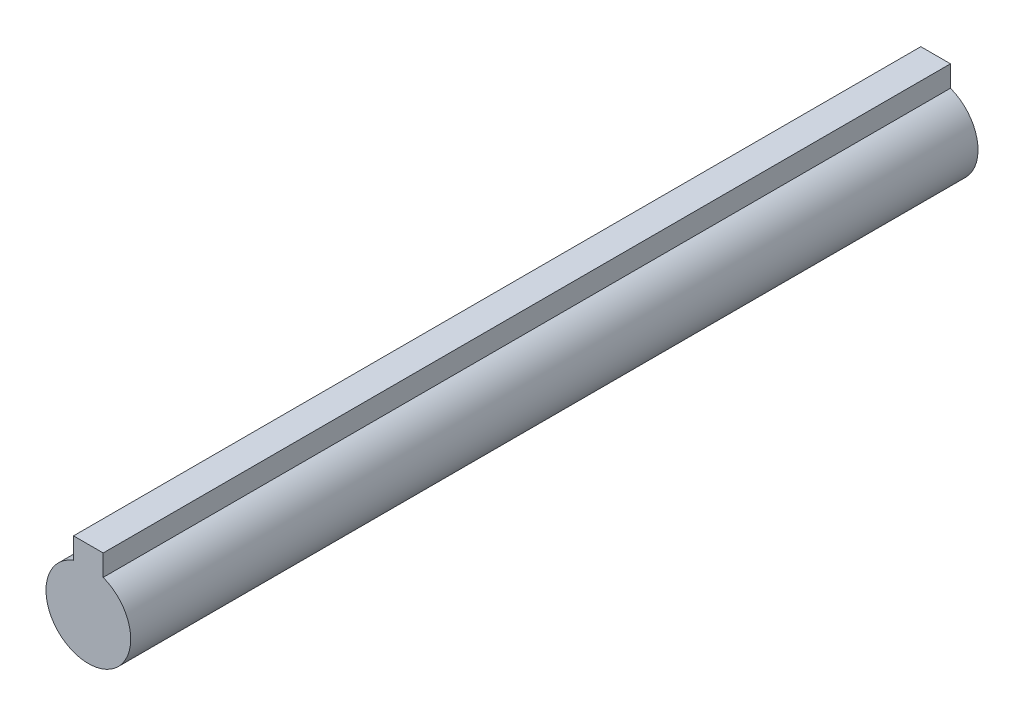
SolidWorks part; units mm, degrees
ref_plane "Alzado" through (0, 0, 0) normal (0, 0, 1) x (1, 0, 0)
ref_plane "Planta" through (0, 0, 0) normal (0, 1, 0) x (1, 0, 0)
ref_plane "Vista lateral" through (0, 0, 0) normal (1, 0, 0) x (0, 0, -1)
sketch "Croquis1" plane through (0, 0, 0) normal (0, 0, 1) x (1, 0, 0)
  line L0 (-3.5, 14.3675) -> (3.5, 14.3675)
  line L1 (-3.5, 14.3675) -> (-3.5, 9.3675)
  line L2 (3.5, 14.3675) -> (3.5, 9.3675)
  arc A0 (-3.5, 9.3675) -> (3.5, 9.3675) centre (0, 0) ccw
  dimension "D1" = 10
  dimension "D2" = 7
  dimension "D3" = 5
extrude "Saliente-Extruir1" add sketch "Croquis1" against normal mid plane 200
